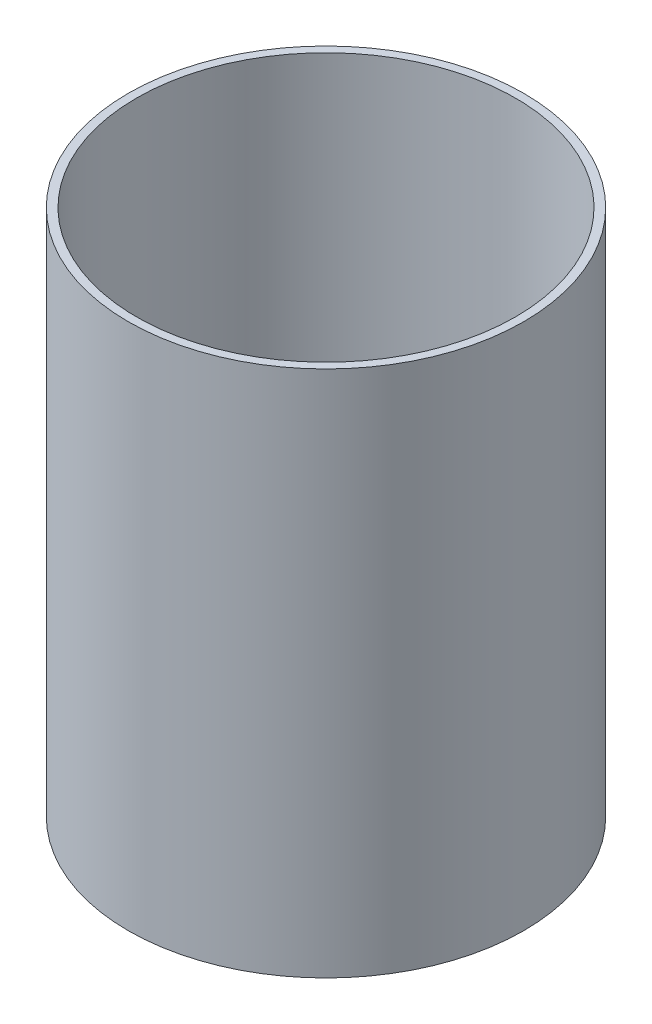
SolidWorks part; units mm, degrees
material "Glass"
ref_plane "Front Plane" through (0, 0, 0) normal (0, 0, 1) x (1, 0, 0)
ref_plane "Top Plane" through (0, 0, 0) normal (0, 1, 0) x (1, 0, 0)
ref_plane "Right Plane" through (0, 0, 0) normal (1, 0, 0) x (0, 0, -1)
sketch "Sketch1" plane through (0, 0, 0) normal (0, 0, 1) x (1, 0, 0)
  line L0 (0, -1000) -> (0, 49000) construction
  line L1 (36.5125, 101.6) -> (36.5125, 3.175)
  line L2 (36.5125, 3.175) -> (0, 3.175)
  line L3 (0, 3.175) -> (0, 0)
  line L4 (0, 0) -> (38.1, 0)
  line L5 (38.1, 0) -> (38.1, 101.6)
  line L6 (38.1, 101.6) -> (36.5125, 101.6)
  dimension "D1" = 101.6
  dimension "D2" = 76.2
  dimension "D3" = 1.5875
  dimension "D4" = 3.175
revolve "Revolve1" add sketch "Sketch1" angle 360 about L0
